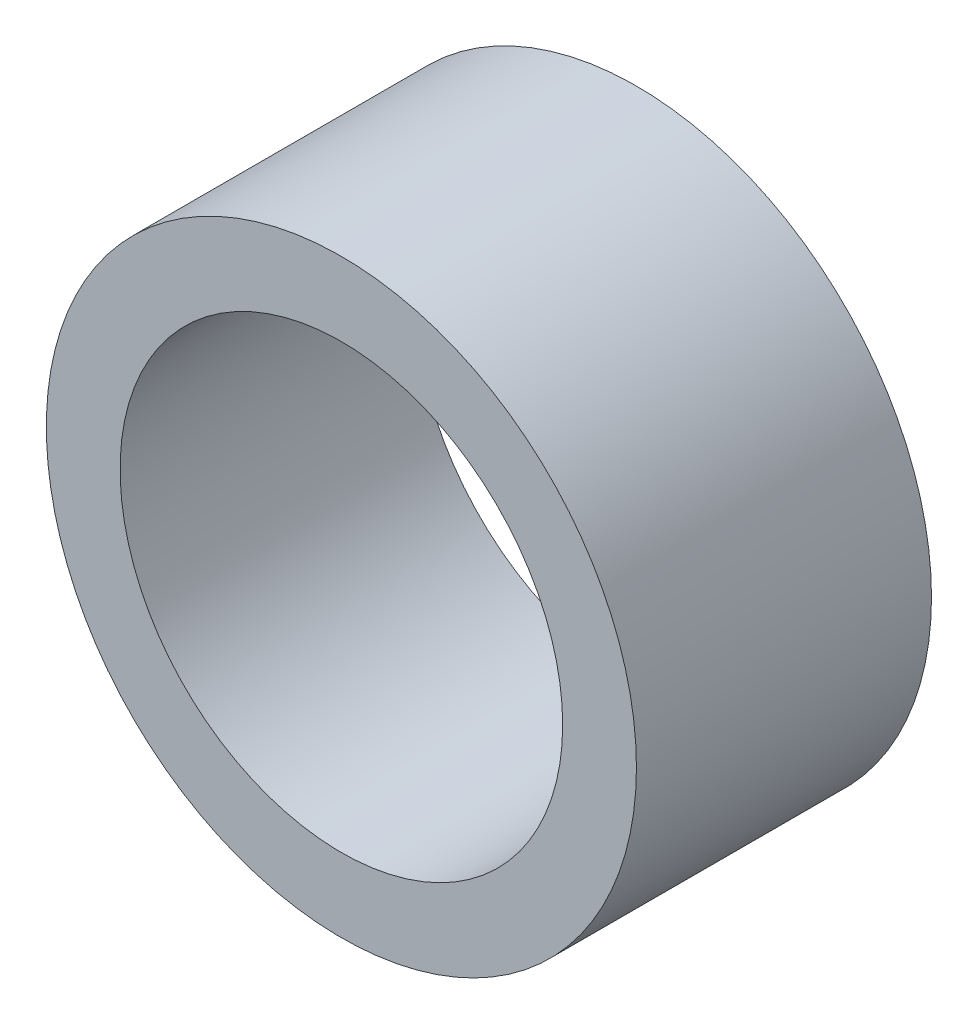
SolidWorks part; units mm, degrees
material "Brass"
ref_plane "Front Plane" through (0, 0, 0) normal (0, 0, 1) x (1, 0, 0)
ref_plane "Top Plane" through (0, 0, 0) normal (0, 1, 0) x (1, 0, 0)
ref_plane "Right Plane" through (0, 0, 0) normal (1, 0, 0) x (0, 0, -1)
sketch "Sketch1" plane through (0, 0, 0) normal (0, 0, 1) x (1, 0, 0)
  circle A0 centre (0, 0) radius 12.7
  circle A1 centre (0, 0) radius 9.525
  dimension "D1" = 25.4
  dimension "D2" = 19.05
extrude "Extrude1" add sketch "Sketch1" along normal blind 12.7
